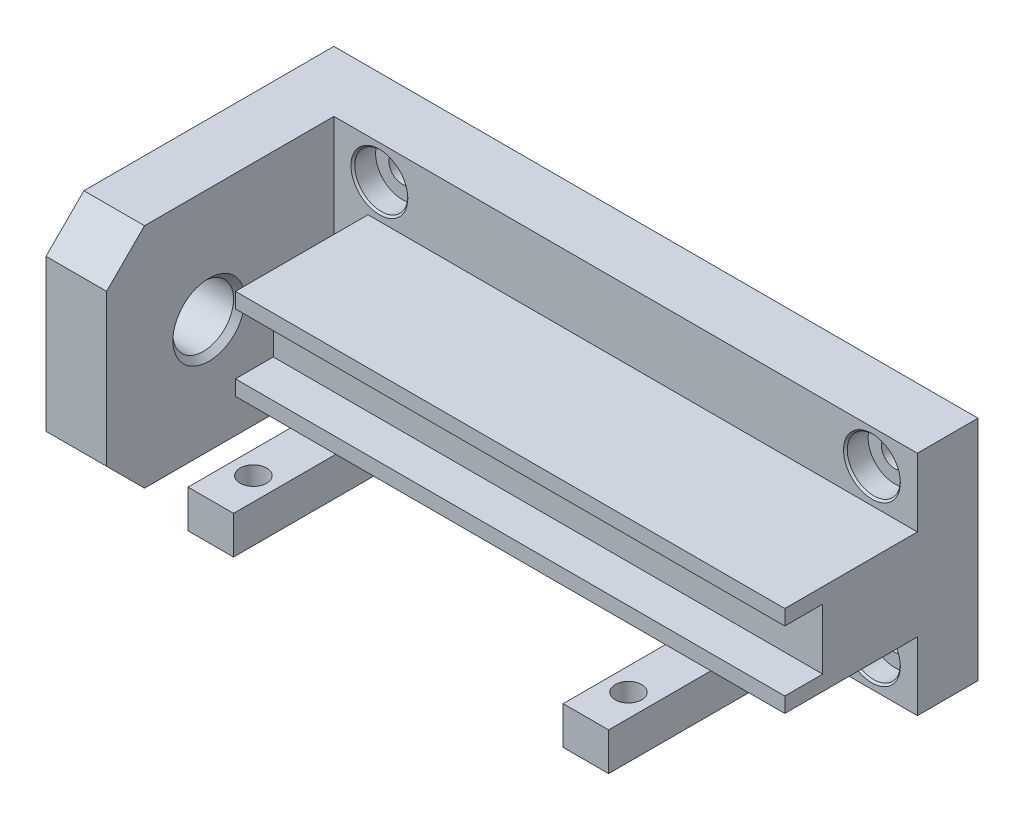
SolidWorks part; units mm, degrees
ref_plane "Planta" through (0, 0, 0) normal (0, 0, 1) x (1, 0, 0)
ref_plane "Alzado" through (0, 0, 0) normal (0, 1, 0) x (1, 0, 0)
ref_plane "Perfil Izquierdo" through (0, 0, 0) normal (1, 0, 0) x (0, 0, -1)
sketch "Croquis1" plane through (0, 0, 0) normal (0, 0, 1) x (1, 0, 0)
  line L0 (42.5, -15) -> (-42.5, 15) construction
  line L1 (-42.5, 15) -> (42.5, 15)
  line L2 (-42.5, 15) -> (-42.5, -15)
  line L3 (-42.5, -15) -> (42.5, -15)
  line L4 (42.5, 15) -> (42.5, -15)
  dimension "D1" = 30
  dimension "D2" = 85
extrude "Extruir1" add sketch "Croquis1" along normal blind 8
sketch "Croquis2" plane through (0, 0, 8) normal (0, 0, 1) x (1, 0, 0)
  line L0 (-42.5, -15) -> (42.5, -15) construction
  line L1 (-42.5, 15) -> (-34.5, 15)
  line L2 (-42.5, 15) -> (-42.5, -15)
  line L3 (-42.5, -15) -> (-34.5, -15)
  line L4 (-34.5, 15) -> (-34.5, -15)
  dimension "D1" = 8
extrude "Extruir2" add sketch "Croquis2" along normal blind 30
sketch "Croquis3" plane through (0, 0, 8) normal (0, 0, 1) x (1, 0, 0)
  line L0 (42.5, -15) -> (42.5, 15) construction
  line L1 (42.5, 6) -> (-30, 6)
  line L2 (42.5, 6) -> (42.5, -6)
  line L3 (42.5, -6) -> (-30, -6)
  line L4 (-30, 6) -> (-30, -6)
  line L5 (42.5, 15) -> (-34.5, 15) construction
  dimension "D1" = 12
  dimension "D2" = 9
  dimension "D3" = 72.5
extrude "Extruir3" add sketch "Croquis3" along normal blind 17.5
sketch "Croquis4" plane through (42.5, 0, 0) normal (1, 0, 0) x (0, 0, -1)
  line L0 (-25.5, -6) -> (-25.5, 6) construction
  line L1 (-25.5, -4) -> (-20.5, -4)
  line L2 (-25.5, -4) -> (-25.5, 4)
  line L3 (-25.5, 4) -> (-20.5, 4)
  line L4 (-20.5, -4) -> (-20.5, 4)
  line L5 (-25.5, -6) -> (-8, -6) construction
  line L6 (-25.5, 6) -> (-8, 6) construction
  dimension "D1" = 2
  dimension "D2" = 2
  dimension "D3" = 5
extrude "Cortar-Extruir1" cut sketch "Croquis4" against normal up to surface (72.5 mm away) up to face at (-30, 0, 16.75)
chamfer "Chaflán1" distance 5 angle 45 2 edges at (-38.5, -15, 38) (-38.5, 15, 38)
sketch "Croquis5" plane through (-34.5, 0, 0) normal (1, 0, 0) x (0, 0, -1)
  line L0 (0, 0) -> (-68.8712, 0) construction
  line L1 (-8, -15) -> (-8, 15) construction
  circle A0 centre (-24.5, 0) radius 4
  dimension "D1" = 8
  dimension "D2" = 16.5
extrude "Cortar-Extruir2" cut sketch "Croquis5" against normal blind 20
chamfer "Chaflán2" distance 0.75 angle 45 2 edges at (-42.5, 0, 20.5) (-34.5, 4, 24.5)
hole_wizard "Refrentado para tornillo de cabeza allen de M6-1" positions "Croquis8" profile "Croquis7" counterbore size "M6" standard "DIN" end condition through all
sketch "Croquis8" plane through (0, 0, 8) normal (0, 0, 1) x (1, 0, 0)
  line L0 (42.5, 15) -> (-34.5, 15) construction
  line L1 (-34.5, -15) -> (42.5, -15) construction
  line L2 (-34.5, -15) -> (42.5, -15) construction
  line L3 (42.5, 6) -> (42.5, 15) construction
  line L4 (42.5, -15) -> (42.5, -6) construction
  point P0 (-28.5, 10.5)
  point P1 (-28.5, -10.5)
  point P2 (36.5, -10.5)
  point P3 (36.5, 10.5)
  dimension "D1" = 4.5
  dimension "D2" = 4.5
  dimension "D3" = 4.5
  dimension "D4" = 4.5
  dimension "D5" = 6
  dimension "D6" = 6
  dimension "D7" = 65
  dimension "D8" = 65
sketch "Croquis7" plane through (-28.5, 10.5, 8) normal (1, 0, 0) x (0, -1, 0)
  line L0 (0, 0) -> (0, 8)
  line L1 (0, 8) -> (1.75, 8)
  line L3 (1.75, 8) -> (1.75, 3)
  line L4 (1.75, 3) -> (3.5, 3)
  line L5 (3.5, 3) -> (3.5, 0)
  line L7 (3.5, 0) -> (0, 0)
  line L11 (0, -6.35) -> (0, 107.95) construction
  dimension "Diámetro de taladro hasta el siguiente" = 3.5
  dimension "Profundidad de taladro hasta el siguiente" = 8
  dimension "Diámetro de refrentado" = 7
  dimension "Profundidad de refrentado" = 3
chamfer "Chaflán3" distance 0.25 angle 45 4 edges at (40, -10.5, 8) (40, 10.5, 8) (-25, -10.5, 8) (-25, 10.5, 8)
sketch "Croquis9" plane through (0, 0, 8) normal (0, 0, 1) x (1, 0, 0)
  line L0 (-23.75, -12) -> (-17.75, -12)
  line L5 (-23.75, -12) -> (-23.75, -7)
  line L7 (-23.75, -7) -> (-17.75, -7)
  line L8 (25.75, -12) -> (31.75, -12)
  line L9 (25.75, -12) -> (25.75, -7)
  line L10 (25.75, -7) -> (31.75, -7)
  line L11 (31.75, -12) -> (31.75, -7)
  line L12 (-17.75, -12) -> (-17.75, -7)
  line L13 (-23.75, -7) -> (-17.75, -12) construction
  line L14 (-17.75, -7) -> (-23.75, -12) construction
  line L15 (25.75, -7) -> (31.75, -12) construction
  line L16 (31.75, -7) -> (25.75, -12) construction
  line L17 (42.5, -15) -> (42.5, -6) construction
  line L18 (-30, -6) -> (42.5, -6) construction
  point P10 (-20.75, -9.5)
  point P11 (28.75, -9.5)
  dimension "D1" = 6
  dimension "D2" = 5
  dimension "D3" = 6
  dimension "D4" = 5
  dimension "D5" = 1
  dimension "D6" = 49.5
  dimension "D7" = 10.75
extrude "Saliente-Extruir1" add sketch "Croquis9" along normal blind 30
sketch "Croquis10" plane through (0, -7, 0) normal (0, 1, 0) x (1, 0, 0)
  line L0 (-17.75, -8) -> (-23.75, -8) construction
  line L1 (-23.75, -38) -> (-23.75, -8) construction
  circle A0 centre (-20.75, -32.38) radius 1.75
  dimension "D1" = 3.5
  dimension "D2" = 24.38
  dimension "D3" = 3
extrude "Cortar-Extruir3" cut sketch "Croquis10" against normal blind 5
sketch "Croquis11" plane through (0, -7, 0) normal (0, 1, 0) x (1, 0, 0)
  line L0 (31.75, -38) -> (31.75, -8) construction
  line L2 (31.75, -8) -> (25.75, -8) construction
  circle A0 centre (28.75, -32.38) radius 1.75
  dimension "D1" = 3.5
  dimension "D2" = 3
  dimension "D3" = 24.38
extrude "Cortar-Extruir4" cut sketch "Croquis11" against normal blind 5
